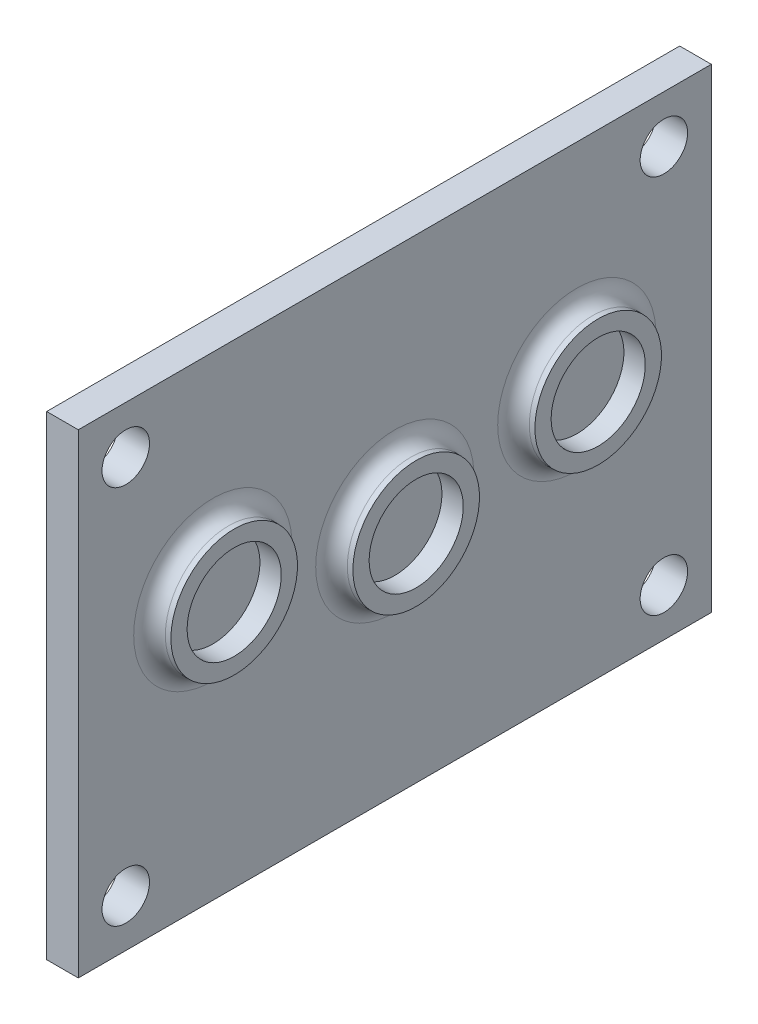
SolidWorks part; units mm, degrees
ref_plane "Front Plane" through (0, 0, 0) normal (0, 0, 1) x (1, 0, 0)
ref_plane "Top Plane" through (0, 0, 0) normal (0, 1, 0) x (1, 0, 0)
ref_plane "Right Plane" through (0, 0, 0) normal (1, 0, 0) x (0, 0, -1)
sketch "Sketch2" plane through (0, 0, 0) normal (1, 0, 0) x (0, 0, -1)
  line L1 (0, 0) -> (40, 0)
  line L2 (0, 0) -> (0, 30)
  line L3 (0, 30) -> (40, 30)
  line L4 (40, 0) -> (40, 30)
  dimension "D1" = 40
  dimension "D2" = 30
extrude "Boss-Extrude1" add sketch "Sketch2" along normal blind 2
sketch "Sketch3" plane through (2, 0, 0) normal (1, 0, 0) x (0, 0, -1)
  line L0 (0, 15) -> (40, 15) construction
  line L1 (0, 30) -> (0, 0) construction
  line L2 (40, 0) -> (40, 30) construction
  line L3 (0, 17) -> (40, 17) construction
  line L4 (0, 13) -> (40, 13) construction
  circle A0 centre (8.5, 17) radius 2.975
  circle A1 centre (20, 15) radius 2.975
  circle A2 centre (31.5, 17) radius 2.975
  circle A3 centre (8.5, 17) radius 4
  circle A4 centre (20, 15) radius 4
  circle A5 centre (31.5, 17) radius 4
  dimension "D3" = 5.95
  dimension "D6" = 8
  dimension "D1" = 2
  dimension "D2" = 2
  dimension "D4" = 8.5
  dimension "D5" = 8.5
extrude "Boss-Extrude2" add sketch "Sketch3" along normal blind 1.35
fillet "Fillet1" radius 1 3 edges at (2, 17, -4.5) (2, 17, -27.5) (2, 15, -16)
sketch "Sketch4" plane through (0, 0, 0) normal (-1, 0, 0) x (0, 0, 1)
  line L0 (-40, 27) -> (0, 27) construction
  line L1 (-40, 0) -> (-40, 30) construction
  line L2 (0, 30) -> (0, 0) construction
  line L3 (-40, 3) -> (0, 3) construction
  line L4 (-37, 30) -> (-37, 0) construction
  line L5 (-40, 30) -> (0, 30) construction
  line L6 (0, 0) -> (-40, 0) construction
  line L7 (-3, 30) -> (-3, 0) construction
  circle A0 centre (-37, 27) radius 1.5
  circle A1 centre (-3, 27) radius 1.5
  circle A2 centre (-37, 3) radius 1.5
  circle A3 centre (-3, 3) radius 1.5
  dimension "D1" = 3
  dimension "D2" = 3
  dimension "D3" = 3
  dimension "D4" = 3
extrude "Cut-Extrude1" cut sketch "Sketch4" against normal blind 2
